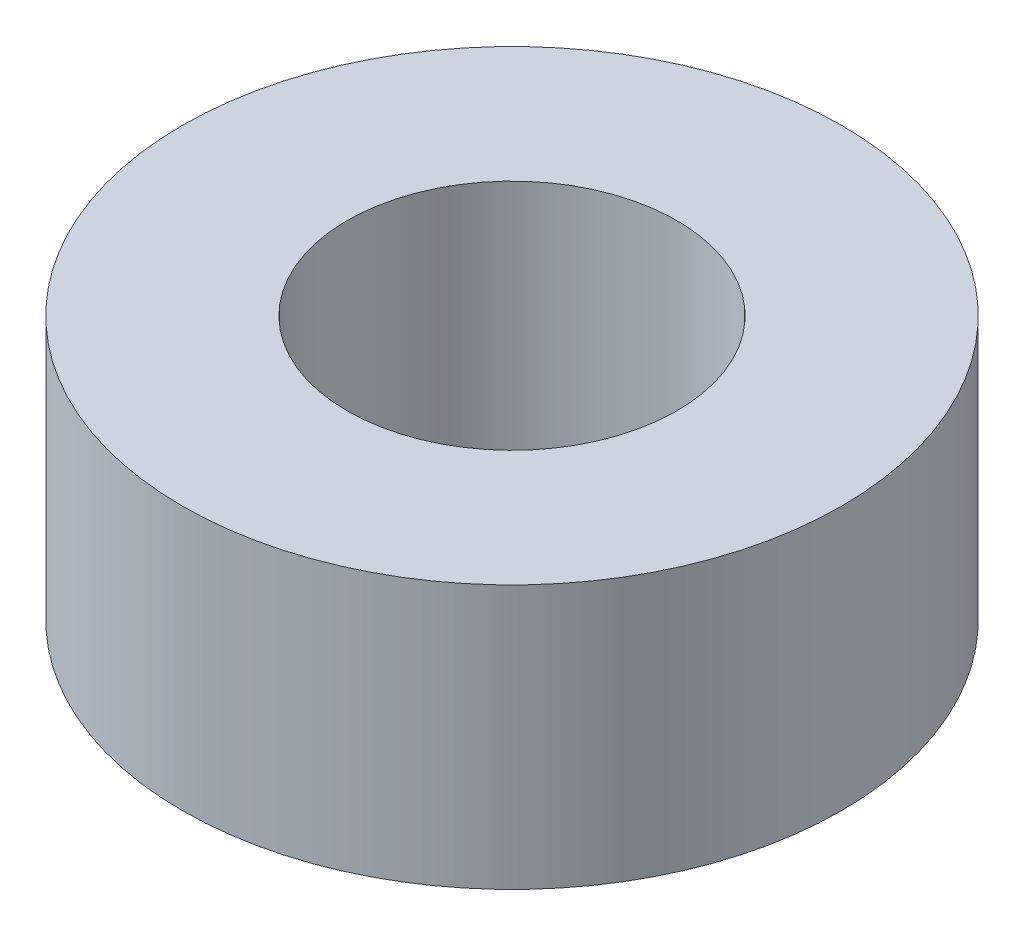
SolidWorks part; units mm, degrees
material "AISI 304"
ref_plane "前视基准面" through (0, 0, 0) normal (0, 0, 1) x (1, 0, 0)
ref_plane "上视基准面" through (0, 0, 0) normal (0, 1, 0) x (1, 0, 0)
ref_plane "右视基准面" through (0, 0, 0) normal (1, 0, 0) x (0, 0, -1)
other "Configuration Table"
sketch "草图1" plane through (0, 0, 0) normal (0, 1, 0) x (1, 0, 0)
  circle A0 centre (0, 0) radius 5
  circle A1 centre (0, 0) radius 2.5
  dimension "D1" = 5
  dimension "D2" = 10
extrude "凸台-拉伸1" add sketch "草图1" along normal blind 4
